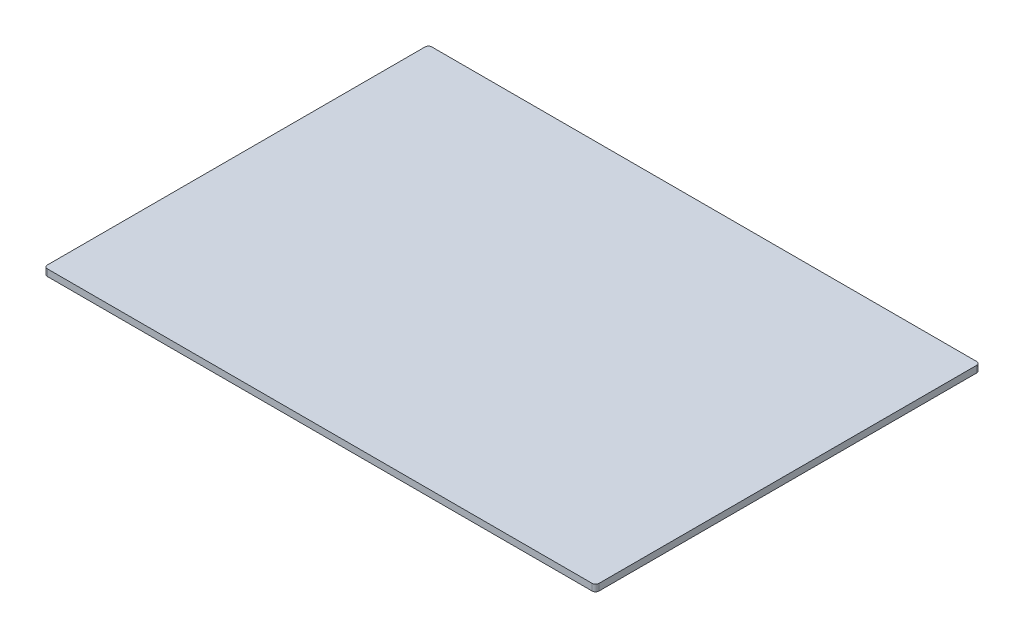
SolidWorks part; units mm, degrees
ref_plane "Front Plane" through (0, 0, 0) normal (0, 0, 1) x (1, 0, 0)
ref_plane "Top Plane" through (0, 0, 0) normal (0, 1, 0) x (1, 0, 0)
ref_plane "Right Plane" through (0, 0, 0) normal (1, 0, 0) x (0, 0, -1)
sketch "Sketch1" plane through (0, 0, 0) normal (0, 1, 0) x (1, 0, 0)
  line L1 (-82.5, 57.5) -> (82.5, 57.5)
  line L2 (-82.5, 57.5) -> (-82.5, -57.5)
  line L3 (-82.5, -57.5) -> (82.5, -57.5)
  line L4 (82.5, 57.5) -> (82.5, -57.5)
  line L5 (-82.5, 57.5) -> (82.5, -57.5) construction
  line L6 (-82.5, -57.5) -> (82.5, 57.5) construction
  point P0 (0, 0)
  dimension "D1" = 165
  dimension "D2" = 115
extrude "Boss-Extrude1" add sketch "Sketch1" along normal blind 2
fillet "Fillet1" radius 1 4 edges at (-82.5, 1, -57.5) (82.5, 1, -57.5) (82.5, 1, 57.5) (-82.5, 1, 57.5)
